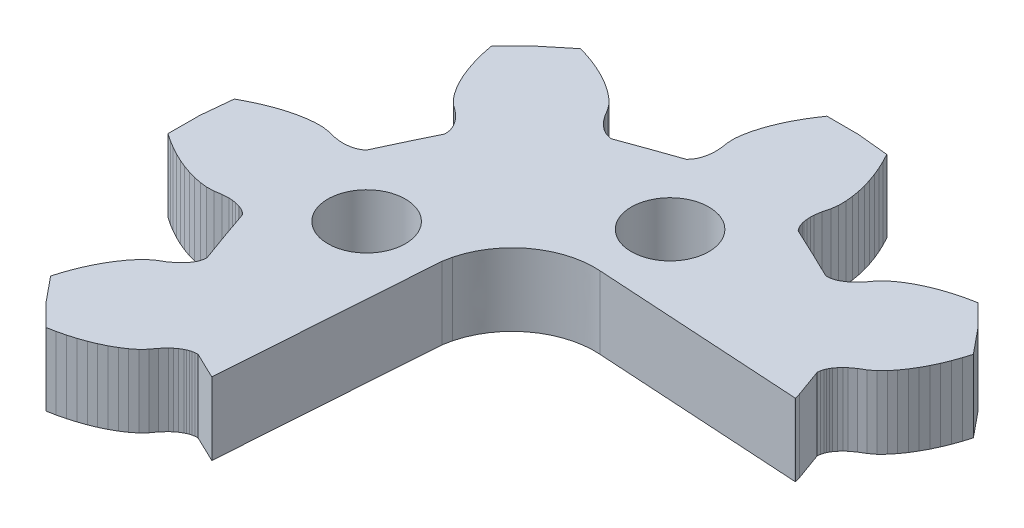
SolidWorks part; units mm, degrees
material "Acrylic (Medium-high impact)"
ref_plane "Front Plane" through (0, 0, 0) normal (0, 0, 1) x (1, 0, 0)
ref_plane "Top Plane" through (0, 0, 0) normal (0, 1, 0) x (1, 0, 0)
ref_plane "Right Plane" through (0, 0, 0) normal (1, 0, 0) x (0, 0, -1)
sketch "Sketch1" plane through (0, 0, 0) normal (0, 1, 0) x (1, 0, 0)
  line L0 (-5.6026, -11.6468) -> (-2.2026, -11.647) construction
  line L1 (-0.7341, -11.5023) -> (-1.3906, -20.9479)
  line L2 (-1.3906, -20.9479) -> (-2.5456, -20.3908)
  line L3 (-2.5456, -20.3908) -> (-2.6799, -20.3943)
  line L4 (-2.6799, -20.3943) -> (-2.7885, -20.4138)
  line L5 (-2.7885, -20.4138) -> (-2.8834, -20.4416)
  line L6 (-2.8834, -20.4416) -> (-2.9692, -20.4755)
  line L7 (-2.9692, -20.4755) -> (-3.0484, -20.5136)
  line L8 (-3.0484, -20.5136) -> (-3.1918, -20.6)
  line L9 (-3.1918, -20.6) -> (-3.3204, -20.6961)
  line L10 (-3.3204, -20.6961) -> (-3.4376, -20.8005)
  line L11 (-3.4376, -20.8005) -> (-3.6453, -21.0276)
  line L12 (-3.6453, -21.0276) -> (-3.8244, -21.2755)
  line L13 (-3.8244, -21.2755) -> (-4.0347, -21.5008)
  line L14 (-4.0347, -21.5008) -> (-4.2826, -21.698)
  line L15 (-4.2826, -21.698) -> (-4.554, -21.8771)
  line L16 (-4.554, -21.8771) -> (-4.8447, -22.04)
  line L17 (-4.8447, -22.04) -> (-5.1524, -22.1877)
  line L18 (-5.1524, -22.1877) -> (-5.4759, -22.3207)
  line L19 (-5.4759, -22.3207) -> (-5.8134, -22.4388)
  line L20 (-5.8134, -22.4388) -> (-6.1644, -22.5422)
  line L21 (-6.1644, -22.5422) -> (-6.5277, -22.6309)
  line L22 (-6.5277, -22.6309) -> (-6.9028, -22.7046)
  line L23 (-6.9028, -22.7046) -> (-7.8789, -21.7211)
  line L24 (-7.8789, -21.7211) -> (-8.7563, -20.6486)
  line L25 (-8.7563, -20.6486) -> (-8.6452, -20.2823)
  line L26 (-8.6452, -20.2823) -> (-8.5202, -19.9291)
  line L27 (-8.5202, -19.9291) -> (-8.3818, -19.59)
  line L28 (-8.3818, -19.59) -> (-8.2301, -19.2654)
  line L29 (-8.2301, -19.2654) -> (-8.0652, -18.9568)
  line L30 (-8.0652, -18.9568) -> (-7.8872, -18.665)
  line L31 (-7.8872, -18.665) -> (-7.6962, -18.3916)
  line L32 (-7.6962, -18.3916) -> (-7.4906, -18.1394)
  line L33 (-7.4906, -18.1394) -> (-7.2697, -17.9121)
  line L34 (-7.2697, -17.9121) -> (-7.0245, -17.7258)
  line L35 (-7.0245, -17.7258) -> (-6.7603, -17.5721)
  line L36 (-6.7603, -17.5721) -> (-6.5136, -17.3885)
  line L37 (-6.5136, -17.3885) -> (-6.3983, -17.2822)
  line L38 (-6.3983, -17.2822) -> (-6.2896, -17.1639)
  line L39 (-6.2896, -17.1639) -> (-6.1894, -17.0297)
  line L40 (-6.1894, -17.0297) -> (-6.1434, -16.9547)
  line L41 (-6.1434, -16.9547) -> (-6.1011, -16.8725)
  line L42 (-6.1011, -16.8725) -> (-6.0635, -16.7807)
  line L43 (-6.0635, -16.7807) -> (-6.0335, -16.6744)
  line L44 (-6.0335, -16.6744) -> (-6.0163, -16.5409)
  line L45 (-6.0163, -16.5409) -> (-6.4522, -15.3335)
  line L46 (-6.4522, -15.3335) -> (-6.8758, -14.1211)
  line L47 (-6.8758, -14.1211) -> (-6.9733, -14.0286)
  line L48 (-6.9733, -14.0286) -> (-7.0636, -13.9653)
  line L49 (-7.0636, -13.9653) -> (-7.1505, -13.9178)
  line L50 (-7.1505, -13.9178) -> (-7.2351, -13.8809)
  line L51 (-7.2351, -13.8809) -> (-7.3181, -13.8519)
  line L52 (-7.3181, -13.8519) -> (-7.4802, -13.8113)
  line L53 (-7.4802, -13.8113) -> (-7.6392, -13.7882)
  line L54 (-7.6392, -13.7882) -> (-7.7956, -13.7789)
  line L55 (-7.7956, -13.7789) -> (-8.1027, -13.7926)
  line L56 (-8.1027, -13.7926) -> (-8.4043, -13.8406)
  line L57 (-8.4043, -13.8406) -> (-8.712, -13.8513)
  line L58 (-8.712, -13.8513) -> (-9.0266, -13.815)
  line L59 (-9.0266, -13.815) -> (-9.3449, -13.7494)
  line L60 (-9.3449, -13.7494) -> (-9.6655, -13.6587)
  line L61 (-9.6655, -13.6587) -> (-9.9873, -13.5451)
  line L62 (-9.9873, -13.5451) -> (-10.3098, -13.4101)
  line L63 (-10.3098, -13.4101) -> (-10.632, -13.2544)
  line L64 (-10.632, -13.2544) -> (-10.9531, -13.0792)
  line L65 (-10.9531, -13.0792) -> (-11.2728, -12.8844)
  line L66 (-11.2728, -12.8844) -> (-11.5899, -12.6708)
  line L67 (-11.5899, -12.6708) -> (-11.5859, -11.2841)
  line L68 (-11.5859, -11.2841) -> (-11.4494, -9.9038)
  line L69 (-11.4494, -9.9038) -> (-11.1122, -9.7236)
  line L70 (-11.1122, -9.7236) -> (-10.7746, -9.5625)
  line L71 (-10.7746, -9.5625) -> (-10.4372, -9.4206)
  line L72 (-10.4372, -9.4206) -> (-10.1009, -9.2988)
  line L73 (-10.1009, -9.2988) -> (-9.7663, -9.1971)
  line L74 (-9.7663, -9.1971) -> (-9.4346, -9.1169)
  line L75 (-9.4346, -9.1169) -> (-9.1066, -9.0592)
  line L76 (-9.1066, -9.0592) -> (-8.7833, -9.0262)
  line L77 (-8.7833, -9.0262) -> (-8.4666, -9.0223)
  line L78 (-8.4666, -9.0223) -> (-8.1616, -9.064)
  line L79 (-8.1616, -9.064) -> (-7.8664, -9.1427)
  line L80 (-7.8664, -9.1427) -> (-7.5622, -9.1875)
  line L81 (-7.5622, -9.1875) -> (-7.4058, -9.194)
  line L82 (-7.4058, -9.194) -> (-7.2454, -9.1873)
  line L83 (-7.2454, -9.1873) -> (-7.0797, -9.1634)
  line L84 (-7.0797, -9.1634) -> (-6.9944, -9.1429)
  line L85 (-6.9944, -9.1429) -> (-6.9066, -9.1145)
  line L86 (-6.9066, -9.1145) -> (-6.8153, -9.0763)
  line L87 (-6.8153, -9.0763) -> (-6.7188, -9.0226)
  line L88 (-6.7188, -9.0226) -> (-6.6125, -8.9404)
  line L89 (-6.6125, -8.9404) -> (-6.0685, -7.7776)
  line L90 (-6.0685, -7.7776) -> (-5.5124, -6.6205)
  line L91 (-5.5124, -6.6205) -> (-5.5159, -6.4862)
  line L92 (-5.5159, -6.4862) -> (-5.5351, -6.3772)
  line L93 (-5.5351, -6.3772) -> (-5.5632, -6.2821)
  line L94 (-5.5632, -6.2821) -> (-5.5968, -6.1961)
  line L95 (-5.5968, -6.1961) -> (-5.6349, -6.1168)
  line L96 (-5.6349, -6.1168) -> (-5.7211, -5.9731)
  line L97 (-5.7211, -5.9731) -> (-5.8171, -5.8443)
  line L98 (-5.8171, -5.8443) -> (-5.921, -5.7269)
  line L99 (-5.921, -5.7269) -> (-6.1479, -5.519)
  line L100 (-6.1479, -5.519) -> (-6.3951, -5.3394)
  line L101 (-6.3951, -5.3394) -> (-6.6203, -5.1289)
  line L102 (-6.6203, -5.1289) -> (-6.8171, -4.8803)
  line L103 (-6.8171, -4.8803) -> (-6.9959, -4.6084)
  line L104 (-6.9959, -4.6084) -> (-7.1585, -4.3172)
  line L105 (-7.1585, -4.3172) -> (-7.3059, -4.009)
  line L106 (-7.3059, -4.009) -> (-7.4387, -3.6849)
  line L107 (-7.4387, -3.6849) -> (-7.5566, -3.3465)
  line L108 (-7.5566, -3.3465) -> (-7.6601, -2.9953)
  line L109 (-7.6601, -2.9953) -> (-7.7485, -2.6312)
  line L110 (-7.7485, -2.6312) -> (-7.822, -2.2557)
  line L111 (-7.822, -2.2557) -> (-6.8403, -1.2777)
  line L112 (-6.8403, -1.2777) -> (-5.7695, -0.3985)
  line L113 (-5.7695, -0.3985) -> (-5.4038, -0.5099)
  line L114 (-5.4038, -0.5099) -> (-5.0516, -0.6351)
  line L115 (-5.0516, -0.6351) -> (-4.7129, -0.7737)
  line L116 (-4.7129, -0.7737) -> (-4.3891, -0.9259)
  line L117 (-4.3891, -0.9259) -> (-4.0808, -1.0908)
  line L118 (-4.0808, -1.0908) -> (-3.7894, -1.2692)
  line L119 (-3.7894, -1.2692) -> (-3.5169, -1.461)
  line L120 (-3.5169, -1.461) -> (-3.265, -1.6666)
  line L121 (-3.265, -1.6666) -> (-3.0382, -1.8879)
  line L122 (-3.0382, -1.8879) -> (-2.8521, -2.1335)
  line L123 (-2.8521, -2.1335) -> (-2.6988, -2.3982)
  line L124 (-2.6988, -2.3982) -> (-2.5154, -2.6457)
  line L125 (-2.5154, -2.6457) -> (-2.4093, -2.7611)
  line L126 (-2.4093, -2.7611) -> (-2.2912, -2.8698)
  line L127 (-2.2912, -2.8698) -> (-2.1572, -2.9703)
  line L128 (-2.1572, -2.9703) -> (-2.0822, -3.0162)
  line L129 (-2.0822, -3.0162) -> (-2.0004, -3.0586)
  line L130 (-2.0004, -3.0586) -> (-1.9087, -3.0962)
  line L131 (-1.9087, -3.0962) -> (-1.8026, -3.1265)
  line L132 (-1.8026, -3.1265) -> (-1.6695, -3.1437)
  line L133 (-1.6695, -3.1437) -> (-0.4639, -2.7068)
  line L134 (-0.4639, -2.7068) -> (0.746, -2.2826)
  line L135 (0.746, -2.2826) -> (0.8384, -2.185)
  line L136 (0.8384, -2.185) -> (0.9015, -2.0944)
  line L137 (0.9015, -2.0944) -> (0.9489, -2.0072)
  line L138 (0.9489, -2.0072) -> (0.9858, -1.9225)
  line L139 (0.9858, -1.9225) -> (1.015, -1.8396)
  line L140 (1.015, -1.8396) -> (1.0554, -1.677)
  line L141 (1.0554, -1.677) -> (1.0784, -1.5179)
  line L142 (1.0784, -1.5179) -> (1.0878, -1.3612)
  line L143 (1.0878, -1.3612) -> (1.074, -1.0533)
  line L144 (1.074, -1.0533) -> (1.0259, -0.7512)
  line L145 (1.0259, -0.7512) -> (1.0154, -0.443)
  line L146 (1.0154, -0.443) -> (1.0517, -0.128)
  line L147 (1.0517, -0.128) -> (1.1172, 0.191)
  line L148 (1.1172, 0.191) -> (1.2077, 0.5123)
  line L149 (1.2077, 0.5123) -> (1.321, 0.8347)
  line L150 (1.321, 0.8347) -> (1.4558, 1.1578)
  line L151 (1.4558, 1.1578) -> (1.611, 1.4804)
  line L152 (1.611, 1.4804) -> (1.7861, 1.8022)
  line L153 (1.7861, 1.8022) -> (1.9804, 2.1223)
  line L154 (1.9804, 2.1223) -> (2.1938, 2.4402)
  line L155 (2.1938, 2.4402) -> (3.5781, 2.4359)
  line L156 (3.5781, 2.4359) -> (4.9558, 2.2992)
  line L157 (4.9558, 2.2992) -> (5.1356, 1.9615)
  line L158 (5.1356, 1.9615) -> (5.2964, 1.6233)
  line L159 (5.2964, 1.6233) -> (5.438, 1.2853)
  line L160 (5.438, 1.2853) -> (5.5597, 0.9484)
  line L161 (5.5597, 0.9484) -> (5.6612, 0.6134)
  line L162 (5.6612, 0.6134) -> (5.7412, 0.281)
  line L163 (5.7412, 0.281) -> (5.7988, -0.0478)
  line L164 (5.7988, -0.0478) -> (5.8318, -0.3715)
  line L165 (5.8318, -0.3715) -> (5.8357, -0.6888)
  line L166 (5.8357, -0.6888) -> (5.7941, -0.9943)
  line L167 (5.7941, -0.9943) -> (5.7155, -1.2901)
  line L168 (5.7155, -1.2901) -> (5.6708, -1.5949)
  line L169 (5.6708, -1.5949) -> (5.6642, -1.7518)
  line L170 (5.6642, -1.7518) -> (5.671, -1.9123)
  line L171 (5.671, -1.9123) -> (5.6948, -2.0782)
  line L172 (5.6948, -2.0782) -> (5.7153, -2.1638)
  line L173 (5.7153, -2.1638) -> (5.7434, -2.2518)
  line L174 (5.7434, -2.2518) -> (5.7818, -2.3433)
  line L175 (5.7818, -2.3433) -> (5.8354, -2.4398)
  line L176 (5.8354, -2.4398) -> (5.9172, -2.5463)
  line L177 (5.9172, -2.5463) -> (7.0779, -3.0915)
  line L178 (7.0779, -3.0915) -> (8.233, -3.6486)
  line L179 (8.233, -3.6486) -> (8.3674, -3.645)
  line L180 (8.3674, -3.645) -> (8.476, -3.6256)
  line L181 (8.476, -3.6256) -> (8.5709, -3.5976)
  line L182 (8.5709, -3.5976) -> (8.6568, -3.5637)
  line L183 (8.6568, -3.5637) -> (8.7359, -3.5256)
  line L184 (8.7359, -3.5256) -> (8.8793, -3.4395)
  line L185 (8.8793, -3.4395) -> (9.0079, -3.3433)
  line L186 (9.0079, -3.3433) -> (9.1251, -3.2389)
  line L187 (9.1251, -3.2389) -> (9.3326, -3.0118)
  line L188 (9.3326, -3.0118) -> (9.5117, -2.764)
  line L189 (9.5117, -2.764) -> (9.722, -2.5387)
  line L190 (9.722, -2.5387) -> (9.9701, -2.3413)
  line L191 (9.9701, -2.3413) -> (10.2416, -2.1624)
  line L192 (10.2416, -2.1624) -> (10.5322, -1.9994)
  line L193 (10.5322, -1.9994) -> (10.8399, -1.8518)
  line L194 (10.8399, -1.8518) -> (11.1634, -1.7186)
  line L195 (11.1634, -1.7186) -> (11.501, -1.6005)
  line L196 (11.501, -1.6005) -> (11.8519, -1.4969)
  line L197 (11.8519, -1.4969) -> (12.2153, -1.4083)
  line L198 (12.2153, -1.4083) -> (12.5901, -1.3345)
  line L199 (12.5901, -1.3345) -> (13.5663, -2.3182)
  line L200 (13.5663, -2.3182) -> (14.4439, -3.3908)
  line L201 (14.4439, -3.3908) -> (14.3325, -3.7571)
  line L202 (14.3325, -3.7571) -> (14.2077, -4.1102)
  line L203 (14.2077, -4.1102) -> (14.0692, -4.4493)
  line L204 (14.0692, -4.4493) -> (13.9176, -4.774)
  line L205 (13.9176, -4.774) -> (13.7526, -5.0827)
  line L206 (13.7526, -5.0827) -> (13.5747, -5.3744)
  line L207 (13.5747, -5.3744) -> (13.3833, -5.6476)
  line L208 (13.3833, -5.6476) -> (13.178, -5.8998)
  line L209 (13.178, -5.8998) -> (12.957, -6.1272)
  line L210 (12.957, -6.1272) -> (12.7118, -6.3135)
  line L211 (12.7118, -6.3135) -> (12.4476, -6.4669)
  line L212 (12.4476, -6.4669) -> (12.2009, -6.651)
  line L213 (12.2009, -6.651) -> (12.0856, -6.7571)
  line L214 (12.0856, -6.7571) -> (11.9769, -6.8755)
  line L215 (11.9769, -6.8755) -> (11.8768, -7.0096)
  line L216 (11.8768, -7.0096) -> (11.8309, -7.0847)
  line L217 (11.8309, -7.0847) -> (11.7885, -7.1668)
  line L218 (11.7885, -7.1668) -> (11.7512, -7.2586)
  line L219 (11.7512, -7.2586) -> (11.7208, -7.3649)
  line L220 (11.7208, -7.3649) -> (11.7036, -7.4982)
  line L221 (11.7036, -7.4982) -> (12.1397, -8.706)
  line L222 (12.1397, -8.706) -> (12.2183, -8.9597)
  line L223 (12.2183, -8.9597) -> (12.1852, -8.9597)
  line L224 (12.1852, -8.9597) -> (3.085, -8.406)
  line L225 (1.3518, -5.2964) -> (4.7518, -5.2966) construction
  circle A0 centre (3.0518, -5.2965) radius 1.7
  circle A1 centre (-3.9026, -11.6469) radius 1.7
  spline S7 degree 3 poles (-0.6582, -11.1223) (-0.6905, -11.249) (-0.7158, -11.3758) (-0.7341, -11.5023) knots 2 2 2 2 2.065378 2.065378 2.065378 2.065378
  spline S8 degree 3 poles (3.085, -8.406) (1.3795, -8.2896) (-0.2195, -9.4035) (-0.6582, -11.1223) knots 1.11291 1.11291 1.11291 1.11291 2 2 2 2
  dimension "D1" = 3.4
extrude "Boss-Extrude1" add sketch "Sketch1" along normal blind 3.175
